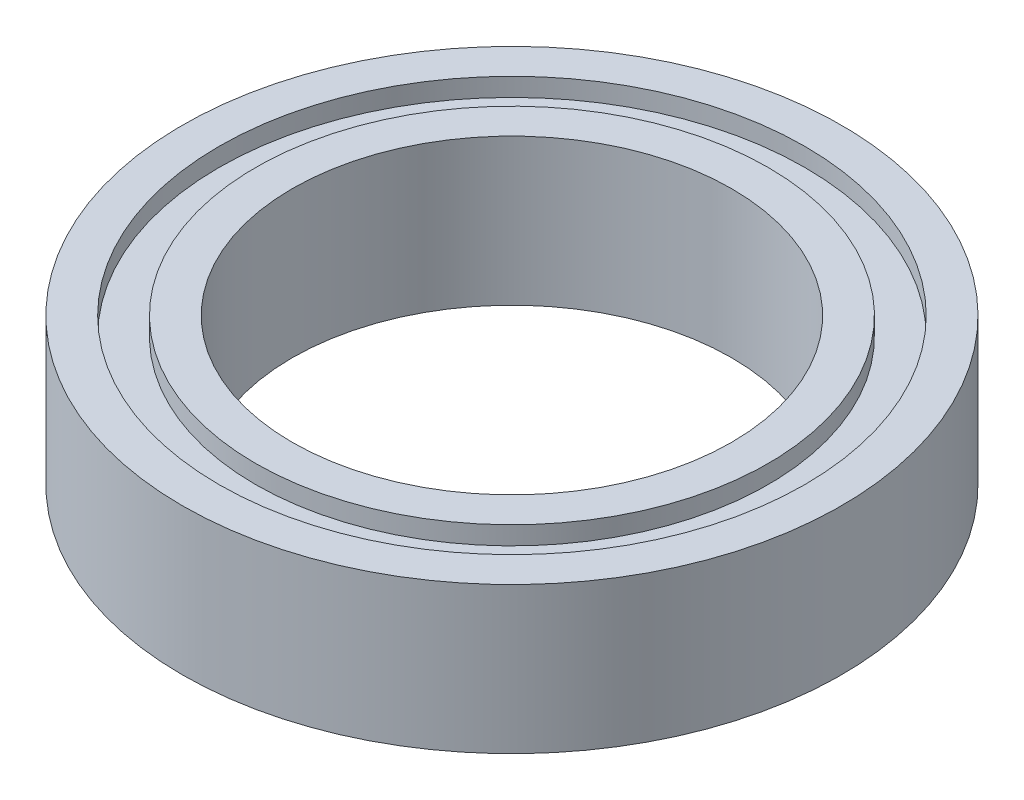
SolidWorks part; units mm, degrees
ref_plane "Front Plane" through (0, 0, 0) normal (0, 0, 1) x (1, 0, 0)
ref_plane "Top Plane" through (0, 0, 0) normal (0, 1, 0) x (1, 0, 0)
ref_plane "Right Plane" through (0, 0, 0) normal (1, 0, 0) x (0, 0, -1)
other "Configuration Table"
sketch "草图1" plane through (0, 0, 0) normal (0, 1, 0) x (1, 0, 0)
  circle A0 centre (0, 0) radius 9
  circle A1 centre (0, 0) radius 6
  dimension "D1" = 18
  dimension "D2" = 12
extrude "凸台-拉伸1" add sketch "草图1" along normal mid plane 4
sketch "草图2" plane through (0, 2, 0) normal (0, 1, 0) x (1, 0, 0)
  circle A0 centre (0, 0) radius 8
  circle A1 centre (0, 0) radius 7
  dimension "D1" = 16
  dimension "D2" = 14
extrude "切除-拉伸1" cut sketch "草图2" against normal blind 0.5
mirror "镜向1" about plane through (0, 0, 0) normal (0, 1, 0) of "切除-拉伸1"
